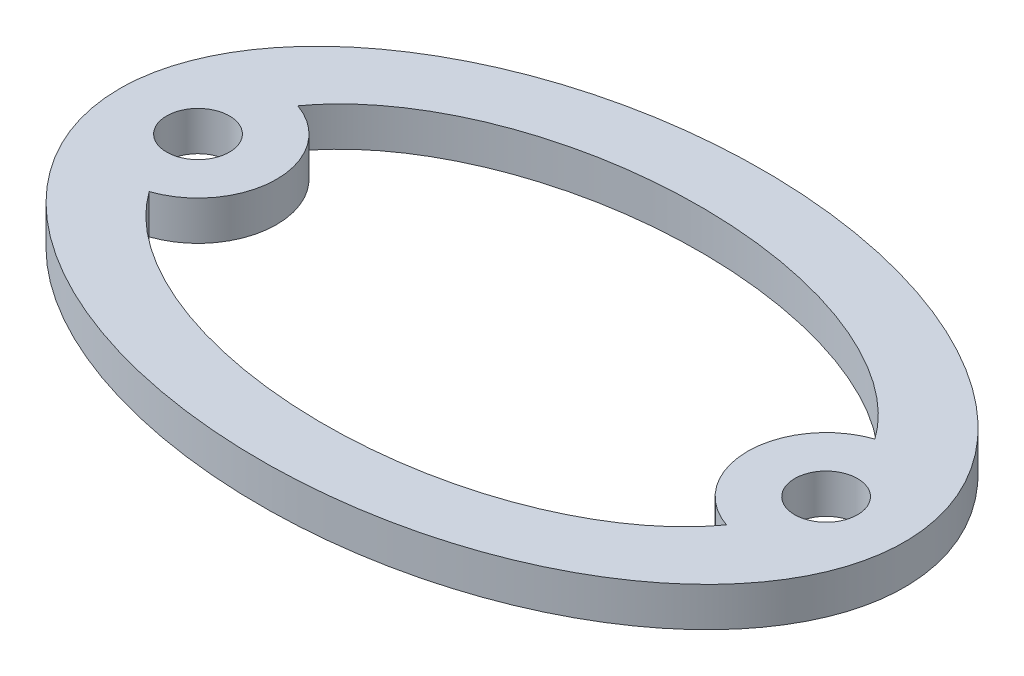
SolidWorks part; units mm, degrees
material "Maple"
ref_plane "Front" through (0, 0, 0) normal (0, 0, 1) x (1, 0, 0)
ref_plane "Top" through (0, 0, 0) normal (0, 1, 0) x (1, 0, 0)
ref_plane "Right" through (0, 0, 0) normal (1, 0, 0) x (0, 0, -1)
sketch "Sketch1" plane through (0, 0, 0) normal (0, 1, 0) x (1, 0, 0)
  line L0 (0, 19.3264) -> (0, -20.8949) construction
  line L1 (-36.9147, 0) -> (38.7102, 0) construction
  circle A0 centre (20, 0) radius 2
  circle A1 centre (-20, 0) radius 2
  arc A2 (-18.3805, 4.7304) -> (-18.3805, -4.7304) centre (-20, 0) cw
  arc A3 (18.3805, 4.7304) -> (18.3805, -4.7304) centre (20, 0) ccw
  ellipse E0 centre (0, 0) end of major axis (-25, 0) minor radius 16
  ellipse E1 centre (0, 0) end of major axis (20, 0) minor radius 12
  dimension "D2" = 4
  dimension "D6" = 5
  dimension "D1" = 40
  dimension "D3" = 50
  dimension "D4" = 16
  dimension "D5" = 12
extrude "Boss-Extrude1" add sketch "Sketch1" along normal blind 2.5 contours E0 E1 A0 A1 | A2 E1 A1 | A0 E1 A3
